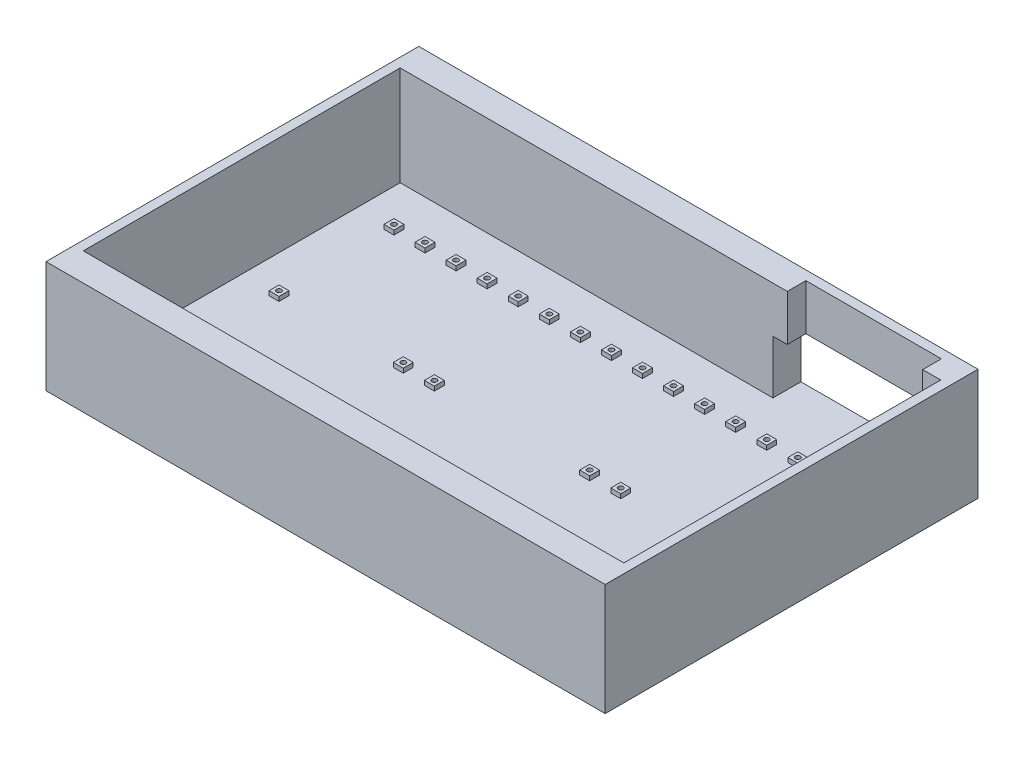
SolidWorks part; units mm, degrees
ref_plane "Front Plane" through (0, 0, 0) normal (0, 0, 1) x (1, 0, 0)
ref_plane "Top Plane" through (0, 0, 0) normal (0, 1, 0) x (1, 0, 0)
ref_plane "Right Plane" through (0, 0, 0) normal (1, 0, 0) x (0, 0, -1)
sketch "Sketch1" plane through (0, 0, 0) normal (0, 1, 0) x (1, 0, 0)
  line L1 (225, -150) -> (-225, -150)
  line L2 (225, -150) -> (225, 150)
  line L3 (225, 150) -> (-225, 150)
  line L4 (-225, -150) -> (-225, 150)
  line L5 (225, -150) -> (-225, 150) construction
  line L6 (225, 150) -> (-225, -150) construction
  point P0 (0, 0)
  dimension "D1" = 450
  dimension "D2" = 300
extrude "Boss-Extrude1" add sketch "Sketch1" along normal blind 90
sketch "Sketch2" plane through (0, 90, 0) normal (0, 1, 0) x (1, 0, 0)
  line L1 (217.5, -127.5) -> (-217.5, -127.5)
  line L2 (217.5, -127.5) -> (217.5, 127.5)
  line L3 (217.5, 127.5) -> (-217.5, 127.5)
  line L4 (-217.5, -127.5) -> (-217.5, 127.5)
  line L5 (217.5, -127.5) -> (-217.5, 127.5) construction
  line L6 (217.5, 127.5) -> (-217.5, -127.5) construction
  point P0 (0, 0)
  dimension "D1" = 255
  dimension "D2" = 435
extrude "Cut-Extrude1" cut sketch "Sketch2" against normal blind 80
sketch "Sketch3" plane through (0, 10, 0) normal (0, 1, 0) x (1, 0, 0)
  line L0 (-158.5, 88.5) -> (-166.5, 88.5)
  line L1 (-183.5, 88.5) -> (-191.5, 88.5)
  line L2 (-183.5, 88.5) -> (-183.5, 96.5)
  line L3 (-183.5, 96.5) -> (-191.5, 96.5)
  line L4 (-191.5, 88.5) -> (-191.5, 96.5)
  line L5 (-183.5, 88.5) -> (-191.5, 96.5) construction
  line L6 (-183.5, 96.5) -> (-191.5, 88.5) construction
  line L7 (-158.5, 88.5) -> (-158.5, 96.5)
  line L8 (-158.5, 96.5) -> (-166.5, 96.5)
  line L9 (-166.5, 88.5) -> (-166.5, 96.5)
  line L10 (-158.5, 88.5) -> (-166.5, 96.5) construction
  line L11 (-158.5, 96.5) -> (-166.5, 88.5) construction
  line L12 (-133.5, 88.5) -> (-141.5, 88.5)
  line L13 (-133.5, 88.5) -> (-133.5, 96.5)
  line L14 (-133.5, 96.5) -> (-141.5, 96.5)
  line L15 (-141.5, 88.5) -> (-141.5, 96.5)
  line L16 (-133.5, 88.5) -> (-141.5, 96.5) construction
  line L17 (-133.5, 96.5) -> (-141.5, 88.5) construction
  line L18 (-108.5, 88.5) -> (-116.5, 88.5)
  line L19 (-108.5, 88.5) -> (-108.5, 96.5)
  line L20 (-108.5, 96.5) -> (-116.5, 96.5)
  line L21 (-116.5, 88.5) -> (-116.5, 96.5)
  line L22 (-108.5, 88.5) -> (-116.5, 96.5) construction
  line L23 (-108.5, 96.5) -> (-116.5, 88.5) construction
  line L24 (-83.5, 88.5) -> (-91.5, 88.5)
  line L25 (-83.5, 88.5) -> (-83.5, 96.5)
  line L26 (-83.5, 96.5) -> (-91.5, 96.5)
  line L27 (-91.5, 88.5) -> (-91.5, 96.5)
  line L28 (-83.5, 88.5) -> (-91.5, 96.5) construction
  line L29 (-83.5, 96.5) -> (-91.5, 88.5) construction
  line L30 (-58.5, 88.5) -> (-66.5, 88.5)
  line L31 (-58.5, 88.5) -> (-58.5, 96.5)
  line L32 (-58.5, 96.5) -> (-66.5, 96.5)
  line L33 (-66.5, 88.5) -> (-66.5, 96.5)
  line L34 (-58.5, 88.5) -> (-66.5, 96.5) construction
  line L35 (-58.5, 96.5) -> (-66.5, 88.5) construction
  line L36 (-33.5, 88.5) -> (-41.5, 88.5)
  line L37 (-33.5, 88.5) -> (-33.5, 96.5)
  line L38 (-33.5, 96.5) -> (-41.5, 96.5)
  line L39 (-41.5, 88.5) -> (-41.5, 96.5)
  line L40 (-33.5, 88.5) -> (-41.5, 96.5) construction
  line L41 (-33.5, 96.5) -> (-41.5, 88.5) construction
  line L42 (-8.5, 88.5) -> (-16.5, 88.5)
  line L43 (-8.5, 88.5) -> (-8.5, 96.5)
  line L44 (-8.5, 96.5) -> (-16.5, 96.5)
  line L45 (-16.5, 88.5) -> (-16.5, 96.5)
  line L46 (-8.5, 88.5) -> (-16.5, 96.5) construction
  line L47 (-8.5, 96.5) -> (-16.5, 88.5) construction
  line L48 (16.5, 88.5) -> (8.5, 88.5)
  line L49 (16.5, 88.5) -> (16.5, 96.5)
  line L50 (16.5, 96.5) -> (8.5, 96.5)
  line L51 (8.5, 88.5) -> (8.5, 96.5)
  line L52 (16.5, 88.5) -> (8.5, 96.5) construction
  line L53 (16.5, 96.5) -> (8.5, 88.5) construction
  line L54 (41.5, 88.5) -> (33.5, 88.5)
  line L55 (41.5, 88.5) -> (41.5, 96.5)
  line L56 (41.5, 96.5) -> (33.5, 96.5)
  line L57 (33.5, 88.5) -> (33.5, 96.5)
  line L58 (41.5, 88.5) -> (33.5, 96.5) construction
  line L59 (41.5, 96.5) -> (33.5, 88.5) construction
  line L60 (66.5, 88.5) -> (58.5, 88.5)
  line L61 (66.5, 88.5) -> (66.5, 96.5)
  line L62 (66.5, 96.5) -> (58.5, 96.5)
  line L63 (58.5, 88.5) -> (58.5, 96.5)
  line L64 (66.5, 88.5) -> (58.5, 96.5) construction
  line L65 (66.5, 96.5) -> (58.5, 88.5) construction
  line L66 (91.5, 88.5) -> (83.5, 88.5)
  line L67 (91.5, 88.5) -> (91.5, 96.5)
  line L68 (91.5, 96.5) -> (83.5, 96.5)
  line L69 (83.5, 88.5) -> (83.5, 96.5)
  line L70 (91.5, 88.5) -> (83.5, 96.5) construction
  line L71 (91.5, 96.5) -> (83.5, 88.5) construction
  line L72 (116.5, 88.5) -> (108.5, 88.5)
  line L73 (116.5, 88.5) -> (116.5, 96.5)
  line L74 (116.5, 96.5) -> (108.5, 96.5)
  line L75 (108.5, 88.5) -> (108.5, 96.5)
  line L76 (116.5, 88.5) -> (108.5, 96.5) construction
  line L77 (116.5, 96.5) -> (108.5, 88.5) construction
  line L78 (141.5, 88.5) -> (133.5, 88.5)
  line L79 (141.5, 88.5) -> (141.5, 96.5)
  line L80 (141.5, 96.5) -> (133.5, 96.5)
  line L81 (133.5, 88.5) -> (133.5, 96.5)
  line L82 (141.5, 88.5) -> (133.5, 96.5) construction
  line L83 (141.5, 96.5) -> (133.5, 88.5) construction
  line L84 (166.5, 88.5) -> (158.5, 88.5)
  line L85 (166.5, 88.5) -> (166.5, 96.5)
  line L86 (166.5, 96.5) -> (158.5, 96.5)
  line L87 (158.5, 88.5) -> (158.5, 96.5)
  line L88 (166.5, 88.5) -> (158.5, 96.5) construction
  line L89 (166.5, 96.5) -> (158.5, 88.5) construction
  line L90 (191.5, 88.5) -> (183.5, 88.5)
  line L91 (191.5, 88.5) -> (191.5, 96.5)
  line L92 (191.5, 96.5) -> (183.5, 96.5)
  line L93 (183.5, 88.5) -> (183.5, 96.5)
  line L94 (191.5, 88.5) -> (183.5, 96.5) construction
  line L95 (191.5, 96.5) -> (183.5, 88.5) construction
  line L96 (217.5, 0) -> (-217.5, 0) construction
  line L97 (-217.5, 127.5) -> (-217.5, -127.5) construction
  line L98 (191.5, -96.5) -> (183.5, -88.5) construction
  line L99 (191.5, -88.5) -> (183.5, -96.5) construction
  line L100 (166.5, -96.5) -> (158.5, -88.5) construction
  line L101 (166.5, -88.5) -> (158.5, -96.5) construction
  line L102 (141.5, -96.5) -> (133.5, -88.5) construction
  line L103 (141.5, -88.5) -> (133.5, -96.5) construction
  line L104 (116.5, -96.5) -> (108.5, -88.5) construction
  line L105 (116.5, -88.5) -> (108.5, -96.5) construction
  line L106 (91.5, -96.5) -> (83.5, -88.5) construction
  line L107 (91.5, -88.5) -> (83.5, -96.5) construction
  line L108 (66.5, -96.5) -> (58.5, -88.5) construction
  line L109 (66.5, -88.5) -> (58.5, -96.5) construction
  line L110 (41.5, -96.5) -> (33.5, -88.5) construction
  line L111 (41.5, -88.5) -> (33.5, -96.5) construction
  line L112 (16.5, -96.5) -> (8.5, -88.5) construction
  line L113 (16.5, -88.5) -> (8.5, -96.5) construction
  line L114 (-8.5, -96.5) -> (-16.5, -88.5) construction
  line L115 (-8.5, -88.5) -> (-16.5, -96.5) construction
  line L116 (-33.5, -96.5) -> (-41.5, -88.5) construction
  line L117 (-33.5, -88.5) -> (-41.5, -96.5) construction
  line L118 (-58.5, -96.5) -> (-66.5, -88.5) construction
  line L119 (-58.5, -88.5) -> (-66.5, -96.5) construction
  line L120 (-83.5, -96.5) -> (-91.5, -88.5) construction
  line L121 (-83.5, -88.5) -> (-91.5, -96.5) construction
  line L122 (-108.5, -96.5) -> (-116.5, -88.5) construction
  line L123 (-108.5, -88.5) -> (-116.5, -96.5) construction
  line L124 (-133.5, -96.5) -> (-141.5, -88.5) construction
  line L125 (-133.5, -88.5) -> (-141.5, -96.5) construction
  line L126 (-158.5, -96.5) -> (-166.5, -88.5) construction
  line L127 (-158.5, -88.5) -> (-166.5, -96.5) construction
  line L128 (-183.5, -96.5) -> (-191.5, -88.5) construction
  line L129 (-183.5, -88.5) -> (-191.5, -96.5) construction
  line L130 (183.5, -88.5) -> (183.5, -96.5)
  line L131 (191.5, -96.5) -> (183.5, -96.5)
  line L132 (191.5, -88.5) -> (191.5, -96.5)
  line L133 (191.5, -88.5) -> (183.5, -88.5)
  line L134 (158.5, -88.5) -> (158.5, -96.5)
  line L135 (166.5, -96.5) -> (158.5, -96.5)
  line L136 (166.5, -88.5) -> (166.5, -96.5)
  line L137 (166.5, -88.5) -> (158.5, -88.5)
  line L138 (133.5, -88.5) -> (133.5, -96.5)
  line L139 (141.5, -96.5) -> (133.5, -96.5)
  line L140 (141.5, -88.5) -> (141.5, -96.5)
  line L141 (141.5, -88.5) -> (133.5, -88.5)
  line L142 (108.5, -88.5) -> (108.5, -96.5)
  line L143 (116.5, -96.5) -> (108.5, -96.5)
  line L144 (116.5, -88.5) -> (116.5, -96.5)
  line L145 (116.5, -88.5) -> (108.5, -88.5)
  line L146 (83.5, -88.5) -> (83.5, -96.5)
  line L147 (91.5, -96.5) -> (83.5, -96.5)
  line L148 (91.5, -88.5) -> (91.5, -96.5)
  line L149 (91.5, -88.5) -> (83.5, -88.5)
  line L150 (58.5, -88.5) -> (58.5, -96.5)
  line L151 (66.5, -96.5) -> (58.5, -96.5)
  line L152 (66.5, -88.5) -> (66.5, -96.5)
  line L153 (66.5, -88.5) -> (58.5, -88.5)
  line L154 (33.5, -88.5) -> (33.5, -96.5)
  line L155 (41.5, -96.5) -> (33.5, -96.5)
  line L156 (41.5, -88.5) -> (41.5, -96.5)
  line L157 (41.5, -88.5) -> (33.5, -88.5)
  line L158 (8.5, -88.5) -> (8.5, -96.5)
  line L159 (16.5, -96.5) -> (8.5, -96.5)
  line L160 (16.5, -88.5) -> (16.5, -96.5)
  line L161 (16.5, -88.5) -> (8.5, -88.5)
  line L162 (-16.5, -88.5) -> (-16.5, -96.5)
  line L163 (-8.5, -96.5) -> (-16.5, -96.5)
  line L164 (-8.5, -88.5) -> (-8.5, -96.5)
  line L165 (-8.5, -88.5) -> (-16.5, -88.5)
  line L166 (-41.5, -88.5) -> (-41.5, -96.5)
  line L167 (-33.5, -96.5) -> (-41.5, -96.5)
  line L168 (-33.5, -88.5) -> (-33.5, -96.5)
  line L169 (-33.5, -88.5) -> (-41.5, -88.5)
  line L170 (-66.5, -88.5) -> (-66.5, -96.5)
  line L171 (-58.5, -96.5) -> (-66.5, -96.5)
  line L172 (-58.5, -88.5) -> (-58.5, -96.5)
  line L173 (-58.5, -88.5) -> (-66.5, -88.5)
  line L174 (-91.5, -88.5) -> (-91.5, -96.5)
  line L175 (-83.5, -96.5) -> (-91.5, -96.5)
  line L176 (-83.5, -88.5) -> (-83.5, -96.5)
  line L177 (-83.5, -88.5) -> (-91.5, -88.5)
  line L178 (-116.5, -88.5) -> (-116.5, -96.5)
  line L179 (-108.5, -96.5) -> (-116.5, -96.5)
  line L180 (-108.5, -88.5) -> (-108.5, -96.5)
  line L181 (-108.5, -88.5) -> (-116.5, -88.5)
  line L182 (-141.5, -88.5) -> (-141.5, -96.5)
  line L183 (-133.5, -96.5) -> (-141.5, -96.5)
  line L184 (-133.5, -88.5) -> (-133.5, -96.5)
  line L185 (-133.5, -88.5) -> (-141.5, -88.5)
  line L186 (-166.5, -88.5) -> (-166.5, -96.5)
  line L187 (-158.5, -96.5) -> (-166.5, -96.5)
  line L188 (-158.5, -88.5) -> (-158.5, -96.5)
  line L189 (-191.5, -88.5) -> (-191.5, -96.5)
  line L190 (-183.5, -96.5) -> (-191.5, -96.5)
  line L191 (-183.5, -88.5) -> (-183.5, -96.5)
  line L192 (-183.5, -88.5) -> (-191.5, -88.5)
  line L193 (-158.5, -88.5) -> (-166.5, -88.5)
  line L194 (-183.5, -4) -> (-191.5, -4)
  line L195 (-183.5, -4) -> (-183.5, 4)
  line L196 (-183.5, 4) -> (-191.5, 4)
  line L197 (-191.5, -4) -> (-191.5, 4)
  line L198 (-183.5, -4) -> (-191.5, 4) construction
  line L199 (-183.5, 4) -> (-191.5, -4) construction
  line L200 (-83.5, -4) -> (-91.5, -4)
  line L201 (-83.5, -4) -> (-83.5, 4)
  line L202 (-83.5, 4) -> (-91.5, 4)
  line L203 (-91.5, -4) -> (-91.5, 4)
  line L204 (317.5, 0) -> (-117.5, 0) construction
  line L205 (-83.5, -4) -> (-91.5, 4) construction
  line L206 (-83.5, 4) -> (-91.5, -4) construction
  line L207 (-58.5, -4) -> (-66.5, -4)
  line L208 (-58.5, -4) -> (-58.5, 4)
  line L209 (-58.5, 4) -> (-66.5, 4)
  line L210 (-66.5, -4) -> (-66.5, 4)
  line L211 (242.5, 0) -> (-192.5, 0) construction
  line L212 (342.5, 0) -> (-92.5, 0) construction
  line L213 (-58.5, -4) -> (-66.5, 4) construction
  line L214 (-58.5, 4) -> (-66.5, -4) construction
  line L215 (0, 0) -> (0, 23.7716) construction
  line L216 (58.5, 4) -> (66.5, -4) construction
  line L217 (58.5, -4) -> (66.5, 4) construction
  line L218 (-342.5, 0) -> (92.5, 0) construction
  line L219 (-242.5, 0) -> (192.5, 0) construction
  line L220 (83.5, 4) -> (91.5, -4) construction
  line L221 (83.5, -4) -> (91.5, 4) construction
  line L222 (-317.5, 0) -> (117.5, 0) construction
  line L223 (183.5, 4) -> (191.5, -4) construction
  line L224 (183.5, -4) -> (191.5, 4) construction
  line L225 (66.5, -4) -> (66.5, 4)
  line L226 (58.5, 4) -> (66.5, 4)
  line L227 (58.5, -4) -> (58.5, 4)
  line L228 (58.5, -4) -> (66.5, -4)
  line L229 (91.5, -4) -> (91.5, 4)
  line L230 (83.5, 4) -> (91.5, 4)
  line L231 (83.5, -4) -> (83.5, 4)
  line L232 (83.5, -4) -> (91.5, -4)
  line L233 (191.5, -4) -> (191.5, 4)
  line L234 (183.5, 4) -> (191.5, 4)
  line L235 (183.5, -4) -> (183.5, 4)
  line L236 (183.5, -4) -> (191.5, -4)
  circle A0 centre (-187.5, 92.5) radius 2
  circle A1 centre (-162.5, 92.5) radius 2
  circle A2 centre (-137.5, 92.5) radius 2
  circle A3 centre (-112.5, 92.5) radius 2
  circle A4 centre (-87.5, 92.5) radius 2
  circle A5 centre (-62.5, 92.5) radius 2
  circle A6 centre (-37.5, 92.5) radius 2
  circle A7 centre (-12.5, 92.5) radius 2
  circle A8 centre (12.5, 92.5) radius 2
  circle A9 centre (37.5, 92.5) radius 2
  circle A10 centre (62.5, 92.5) radius 2
  circle A11 centre (87.5, 92.5) radius 2
  circle A12 centre (112.5, 92.5) radius 2
  circle A13 centre (137.5, 92.5) radius 2
  circle A14 centre (162.5, 92.5) radius 2
  circle A15 centre (187.5, 92.5) radius 2
  circle A16 centre (187.5, -92.5) radius 2
  circle A17 centre (162.5, -92.5) radius 2
  circle A18 centre (137.5, -92.5) radius 2
  circle A19 centre (112.5, -92.5) radius 2
  circle A20 centre (87.5, -92.5) radius 2
  circle A21 centre (62.5, -92.5) radius 2
  circle A22 centre (37.5, -92.5) radius 2
  circle A23 centre (12.5, -92.5) radius 2
  circle A24 centre (-12.5, -92.5) radius 2
  circle A25 centre (-37.5, -92.5) radius 2
  circle A26 centre (-62.5, -92.5) radius 2
  circle A27 centre (-87.5, -92.5) radius 2
  circle A28 centre (-112.5, -92.5) radius 2
  circle A29 centre (-137.5, -92.5) radius 2
  circle A30 centre (-162.5, -92.5) radius 2
  circle A31 centre (-187.5, -92.5) radius 2
  circle A32 centre (-187.5, 0) radius 2
  circle A33 centre (-87.5, 0) radius 2
  circle A34 centre (-62.5, 0) radius 2
  circle A35 centre (62.5, 0) radius 2
  circle A36 centre (87.5, 0) radius 2
  circle A37 centre (187.5, 0) radius 2
  dimension "D1" = 4
  dimension "D2" = 8
  dimension "D3" = 92.5
  dimension "D4" = 187.5
  dimension "D5" = 16
  dimension "D6" = 2
  dimension "D7" = 2
  dimension "D8" = 2
extrude "Boss-Extrude2" add sketch "Sketch3" along normal blind 3.5
sketch "Sketch5" plane through (0, 90, 0) normal (0, 1, 0) x (1, 0, 0)
  line L1 (203, 127.5) -> (94, 127.5)
  line L2 (203, 127.5) -> (203, 142.5)
  line L3 (203, 142.5) -> (94, 142.5)
  line L4 (94, 127.5) -> (94, 142.5)
  point P5 (0, 0)
  dimension "D1" = 109
  dimension "D2" = 15
  dimension "D3" = 14.5
extrude "Cut-Extrude2" cut sketch "Sketch5" against normal up to surface (80 mm away) up to face at (187.5, 10, 0)
sketch "Sketch7" plane through (0, 0, -127.5) normal (0, 0, 1) x (1, 0, 0)
  line L1 (217.5, 10) -> (82.5, 10)
  line L2 (217.5, 10) -> (217.5, 53)
  line L3 (217.5, 53) -> (82.5, 53)
  line L4 (82.5, 10) -> (82.5, 53)
  dimension "D1" = 43
  dimension "D2" = 135
extrude "Cut-Extrude3" cut sketch "Sketch7" against normal through all
ref_plane "Plane1" through (150, 0, 0) normal (1, 0, 0) x (0, 0, -1)
ref_plane "Plane2" through (0, 31.5, 0) normal (0, -1, 0) x (-1, 0, 0)
